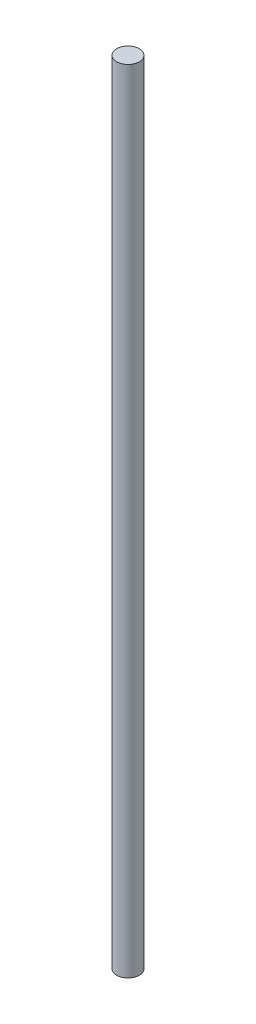
SolidWorks part; units mm, degrees
ref_plane "前视基准面" through (0, 0, 0) normal (0, 0, 1) x (1, 0, 0)
ref_plane "上视基准面" through (0, 0, 0) normal (0, 1, 0) x (1, 0, 0)
ref_plane "右视基准面" through (0, 0, 0) normal (1, 0, 0) x (0, 0, -1)
sketch "草图1" plane through (0, 0, 0) normal (0, 1, 0) x (1, 0, 0)
  circle A0 centre (0, 0) radius 10
  dimension "D1" = 20
extrude "凸台-拉伸1" add sketch "草图1" along normal blind 700
